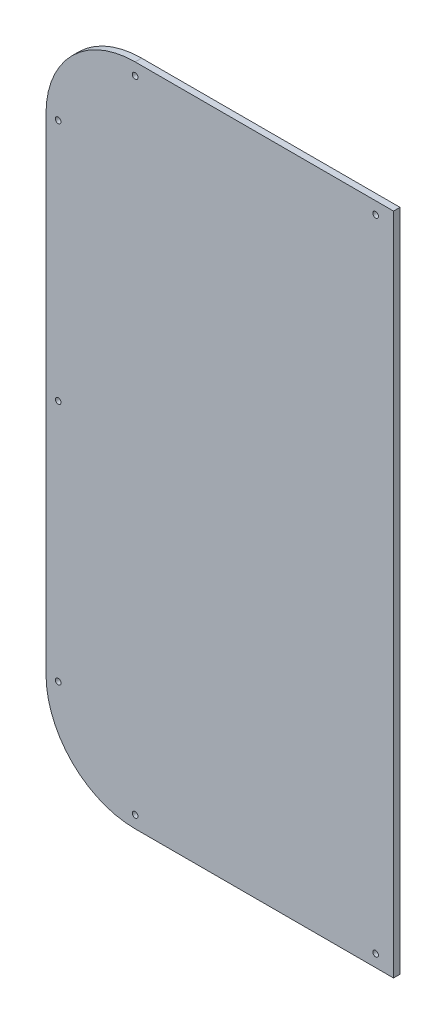
SolidWorks part; units mm, degrees
ref_plane "Front Plane" through (0, 0, 0) normal (0, 0, 1) x (1, 0, 0)
ref_plane "Top Plane" through (0, 0, 0) normal (0, 1, 0) x (1, 0, 0)
ref_plane "Right Plane" through (0, 0, 0) normal (1, 0, 0) x (0, 0, -1)
sketch "Sketch1" plane through (0, 0, 0) normal (0, 0, 1) x (1, 0, 0)
  line L0 (2023.8217, 383.9488) -> (1864.3217, 383.9488) construction
  line L1 (1816.8217, 336.4488) -> (1816.8217, 36.4488) construction
  line L2 (1864.3217, -11.0512) -> (2023.8217, -11.0512) construction
  line L9 (2023.8217, 391.4488) -> (2023.8217, -18.5512)
  line L12 (1864.3217, -18.5512) -> (2023.8217, -18.5512)
  line L13 (1809.3217, 336.4488) -> (1809.3217, 36.4488)
  line L14 (2023.8217, 391.4488) -> (1864.3217, 391.4488)
  line L15 (1864.3217, -18.5512) -> (2023.8217, -18.5512)
  line L16 (1809.3217, 336.4488) -> (1809.3217, 36.4488)
  line L17 (2023.8217, 391.4488) -> (1864.3217, 391.4488)
  arc A0 (1864.3217, 383.9488) -> (1816.8217, 336.4488) centre (1864.3217, 336.4488) ccw construction
  arc A1 (1816.8217, 36.4488) -> (1864.3217, -11.0512) centre (1864.3217, 36.4488) ccw construction
  circle A4 centre (2012.7629, -11.0512) radius 1.75
  circle A6 centre (1864.3217, -11.0512) radius 1.75
  circle A7 centre (1816.8217, 36.4488) radius 1.75
  circle A8 centre (1816.8217, 186.4488) radius 1.75
  arc A9 (1809.3217, 36.4488) -> (1864.3217, -18.5512) centre (1864.3217, 36.4488) ccw
  arc A10 (1864.3217, 391.4488) -> (1809.3217, 336.4488) centre (1864.3217, 336.4488) ccw
  arc A11 (1809.3217, 36.4488) -> (1864.3217, -18.5512) centre (1864.3217, 36.4488) ccw
  arc A12 (1864.3217, 391.4488) -> (1809.3217, 336.4488) centre (1864.3217, 336.4488) ccw
  circle A13 centre (1816.8217, 336.4488) radius 1.75
  circle A14 centre (1864.3217, 383.9488) radius 1.75
  circle A15 centre (2012.7629, 383.9488) radius 1.75
  dimension "D1" = 15
extrude "Boss-Extrude1" add sketch "Sketch1" along normal blind 4
